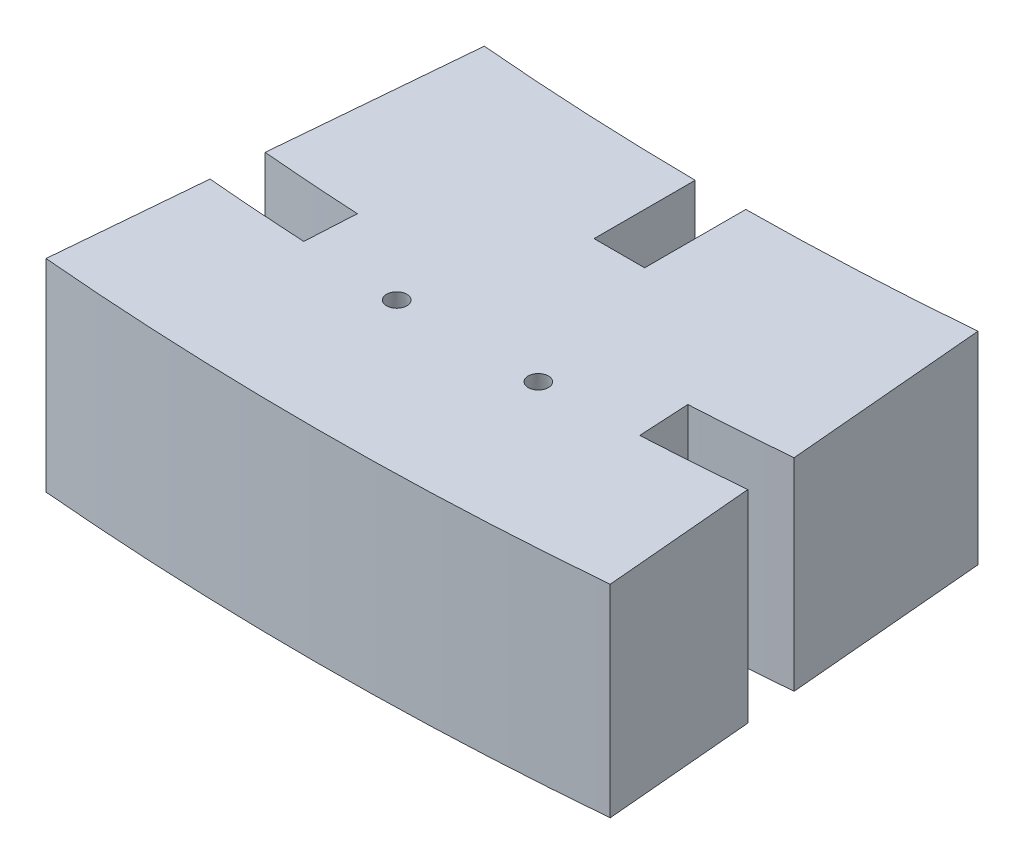
SolidWorks part; units mm, degrees
ref_plane "前视基准面" through (0, 0, 0) normal (0, 0, 1) x (1, 0, 0)
ref_plane "上视基准面" through (0, 0, 0) normal (0, 1, 0) x (1, 0, 0)
ref_plane "右视基准面" through (0, 0, 0) normal (1, 0, 0) x (0, 0, -1)
sketch "草图3" plane through (0, 0, 0) normal (0, 1, 0) x (1, 0, 0)
  line L0 (0, -1400) -> (0, -1600) construction
  line L3 (-139.4492, -1593.9115) -> (-122.018, -1394.6726)
  line L4 (122.018, -1394.6726) -> (139.4492, -1593.9115)
  arc A0 (-122.018, -1394.6726) -> (122.018, -1394.6726) centre (0, 0) ccw
  arc A1 (-139.4492, -1593.9115) -> (139.4492, -1593.9115) centre (0, 0) ccw
  dimension "D1" = 5
  dimension "D2" = 5
extrude "凸台-拉伸1" add sketch "草图3" along normal blind 100
sketch "草图6" plane through (0, 100, 0) normal (0, 1, 0) x (1, 0, 0)
  line L0 (0, 0) -> (0, -1600) construction
  line L1 (-12.5, -1399.9442) -> (12.5, -1399.9442)
  line L2 (0, -1449.9442) -> (12.5, -1449.9442)
  line L3 (12.5, -1449.9442) -> (12.5, -1399.9442)
  line L4 (0, -1449.9442) -> (-12.5, -1449.9442)
  line L5 (-12.5, -1449.9442) -> (-12.5, -1399.9442)
  arc A0 (-139.4492, -1593.9115) -> (139.4492, -1593.9115) centre (0, 0) ccw construction
  arc A1 (-122.018, -1394.6726) -> (122.018, -1394.6726) centre (0, 0) ccw construction
  dimension "D1" = 12.5
  dimension "D2" = 12.5
  dimension "D3" = 50
extrude "切除-拉伸2" cut sketch "草图6" against normal through all
sketch "草图7" plane through (0, 100, 0) normal (0, 1, 0) x (1, 0, 0)
  line L0 (0, 0) -> (0, -1600) construction
  line L1 (0, 0) -> (966.7868, 0)
  line L2 (10, -1500) -> (60, -1500)
  line L3 (10, -1500) -> (10, -1550)
  line L4 (10, -1550) -> (60, -1550)
  line L5 (60, -1500) -> (60, -1550)
  line L6 (10, -1500) -> (60, -1550) construction
  line L7 (10, -1550) -> (60, -1500) construction
  line L8 (-60, -1500) -> (-10, -1500)
  line L9 (-60, -1500) -> (-60, -1550)
  line L10 (-60, -1550) -> (-10, -1550)
  line L11 (-10, -1500) -> (-10, -1550)
  line L12 (-60, -1500) -> (-10, -1550) construction
  line L13 (-60, -1550) -> (-10, -1500) construction
  arc A0 (-139.4492, -1593.9115) -> (139.4492, -1593.9115) centre (0, 0) ccw construction
  point P6 (35, -1525)
  point P11 (-35, -1525)
  point P16 (-10, -1525)
  dimension "D1" = 50
  dimension "D2" = 50
  dimension "D3" = 50
  dimension "D4" = 50
  dimension "D5" = 10
  dimension "D6" = 10
  dimension "D7" = 1500
  dimension "D8" = 1500
ref_plane "基准面1" through (-35, 0, 0) normal (1, 0, 0) x (0, 0, -1)
sketch "草图8" plane through (-35, 0, 0) normal (1, 0, 0) x (0, 0, -1)
  line L0 (-1525, 100) -> (-1530, 100)
  line L1 (-1530, 100) -> (-1538.6824, 50.7596)
  line L2 (-1538.6824, 50.7596) -> (-1538.6824, 0)
  line L3 (-1538.6824, 0) -> (-1525, 0)
  line L4 (-1525, 0) -> (-1525, 100)
  dimension "D1" = 5
  dimension "D2" = 50
  dimension "D3" = 100
  dimension "D4" = 100
revolve "切除-旋转1" cut sketch "草图8" angle 360 about L4
ref_plane "基准面2" through (0, 0, 0) normal (-1, 0, 0) x (0, 0, 1)
mirror "镜向1" about plane through (0, 0, 0) normal (-1, 0, 0) of "切除-旋转1"
sketch "草图9" plane through (0, 100, 0) normal (0, 1, 0) x (1, 0, 0)
  line L0 (81.6751, -1497.7747) -> (83.0448, -1522.8919)
  line L1 (-83.0448, -1522.8919) -> (-81.6751, -1497.7747)
  line L2 (132.926, -1519.3508) -> (130.7336, -1494.292)
  line L3 (-122.018, -1394.6726) -> (-139.4492, -1593.9115) construction
  line L4 (139.4492, -1593.9115) -> (122.018, -1394.6726) construction
  line L5 (-132.926, -1519.3508) -> (-130.7336, -1494.292)
  arc A0 (-130.7336, -1494.292) -> (-81.6751, -1497.7747) centre (0, 0) ccw
  arc A1 (-132.926, -1519.3508) -> (-83.0448, -1522.8919) centre (0, 0) ccw
  arc A2 (83.0448, -1522.8919) -> (132.926, -1519.3508) centre (0, 0) ccw
  arc A3 (81.6751, -1497.7747) -> (130.7336, -1494.292) centre (0, 0) ccw
  dimension "D1" = 50
  dimension "D2" = 50
extrude "切除-拉伸3" cut sketch "草图9" against normal through all
